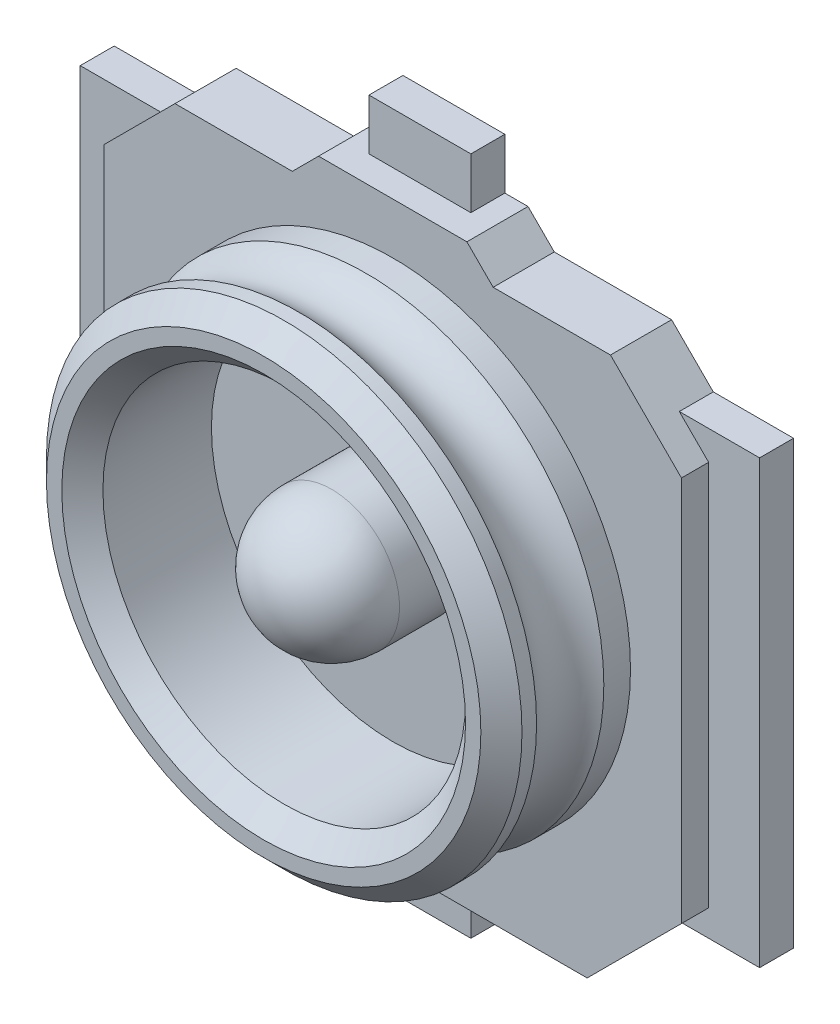
SolidWorks part; units mm, degrees
ref_plane "Front Plane" through (0, 0, 0) normal (0, 0, 1) x (1, 0, 0)
ref_plane "Top Plane" through (0, 0, 0) normal (0, 1, 0) x (1, 0, 0)
ref_plane "Right Plane" through (0, 0, 0) normal (1, 0, 0) x (0, 0, -1)
sketch "Sketch1" plane through (0, 0, 0) normal (0, 0, 1) x (1, 0, 0)
  line L0 (0, 1) -> (-0.15, 1)
  line L1 (-0.15, 1) -> (-0.15, 0.4627)
  line L2 (-0.15, 0.4627) -> (-0.075, 0.4627)
  line L3 (-0.075, 0.4627) -> (-0.075, 0.1956)
  line L4 (0, -0.2095) -> (0, 1)
  line L6 (0, -0.7) -> (-0.15, -0.7)
  line L7 (0, -0.7) -> (0, -1)
  line L8 (0, -1) -> (-0.15, -1)
  line L9 (-0.15, -0.7) -> (-0.15, -1)
  line L10 (-1, -0.65) -> (-0.7, -0.65)
  line L11 (-1, -0.65) -> (-1, 0.65)
  line L12 (-1, 0.65) -> (-0.7, 0.65)
  line L13 (-0.7, -0.65) -> (-0.7, 0.65)
  line L14 (-1, -0.65) -> (-0.7, 0.65) construction
  line L15 (-1, 0.65) -> (-0.7, -0.65) construction
  arc A0 (-0.075, 0.1956) -> (0, -0.2095) centre (0, 0) ccw
  point P12 (-0.85, 0)
  dimension "D1" = 0.15
  dimension "D2" = 2
  dimension "D3" = 1
  dimension "D4" = 0.3
  dimension "D5" = 1.3
  dimension "D6" = 1
  dimension "D7" = 0.3
extrude "Boss-Extrude1" add sketch "Sketch1" along normal blind 0.1
sketch "Sketch2" plane through (0, 0, 0) normal (0, 0, 1) x (1, 0, 0)
  line L10 (0, -0.85) -> (0, 0.85)
  line L11 (0, -0.2095) -> (0, 1) construction
  line L12 (0, 0.85) -> (-0.2183, 0.85)
  line L13 (-0.2183, 0.85) -> (-0.2956, 0.7727)
  line L14 (-0.2956, 0.7727) -> (-0.641, 0.7727)
  line L15 (-0.641, 0.7727) -> (-0.85, 0.5637)
  line L16 (-0.85, 0.5637) -> (-0.85, -0.5724)
  line L17 (-0.85, -0.5724) -> (-0.5724, -0.85)
  line L18 (-0.5724, -0.85) -> (0, -0.85)
  line L19 (-0.7, 0.65) -> (-1, 0.65) construction
  point P16 (-0.85, 0.65)
  dimension "D1" = 0.85
  dimension "D2" = 0.85
  dimension "D3" = 135
  dimension "D4" = 135
extrude "Boss-Extrude2" add sketch "Sketch2" along normal blind 0.18
mirror "Mirror2" about plane through (0, 0, 0) normal (1, 0, 0) of "Boss-Extrude2", "Boss-Extrude1"
sketch "Sketch3" plane through (0, 0, 0) normal (0, 1, 0) x (1, 0, 0)
  line L0 (0, -0.18) -> (0, -0.56)
  line L1 (-0.5724, -0.18) -> (0.5724, -0.18) construction
  line L2 (0, -0.56) -> (0.2, -0.56)
  line L3 (0.2, -0.56) -> (0.2, -0.18)
  line L4 (0.2, -0.18) -> (0, -0.18)
  line L5 (0.5337, -0.18) -> (0.5337, -0.4995)
  line L6 (0.5943, -0.56) -> (0.6395, -0.56)
  line L8 (0.85, -0.18) -> (0.5724, -0.18) construction
  line L9 (0.7, -0.18) -> (0.5337, -0.18)
  line L10 (0.7, -0.4995) -> (0.6395, -0.56)
  line L11 (0.7, -0.2585) -> (0.7, -0.18)
  line L12 (0.7, -0.4995) -> (0.7, -0.4565)
  line L13 (0.5943, -0.56) -> (0.5337, -0.4995)
  arc A1 (0.7, -0.4565) -> (0.7, -0.2585) centre (0.7784, -0.3575) cw
  dimension "D1" = 0.2
  dimension "D2" = 0.7
  dimension "D3" = 135
  dimension "D4" = 135
revolve "Revolve1" add sketch "Sketch3" angle 360 about L0
fillet "Fillet1" radius 0.2 1 edges at (-0.2, 0, 0.56)
